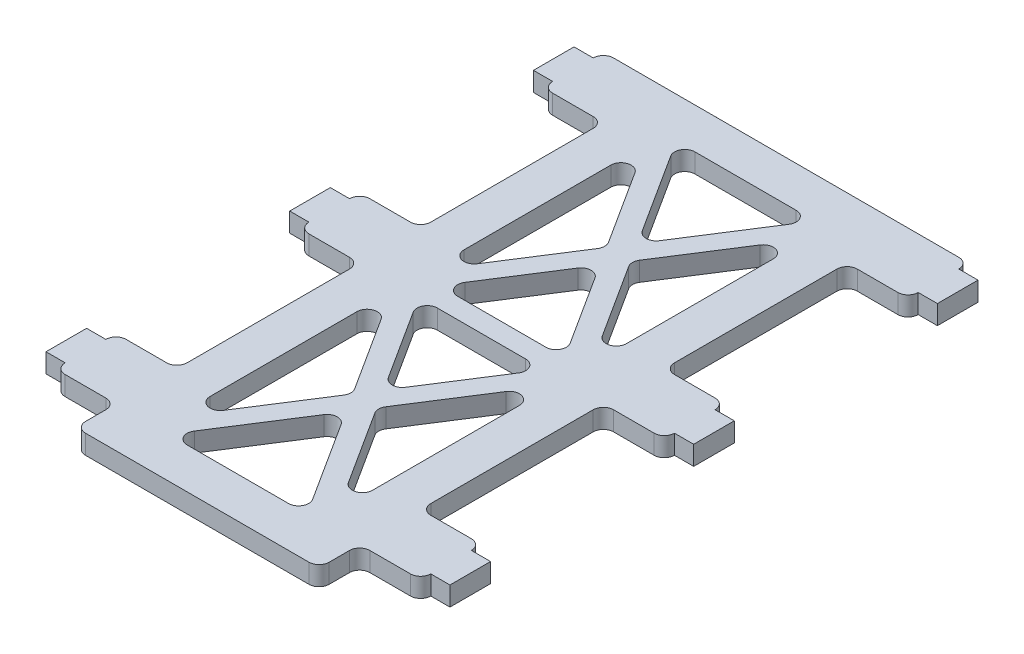
SolidWorks part; units mm, degrees
ref_plane "Front Plane" through (0, 0, 0) normal (0, 0, 1) x (1, 0, 0)
ref_plane "Top Plane" through (0, 0, 0) normal (0, 1, 0) x (1, 0, 0)
ref_plane "Right Plane" through (0, 0, 0) normal (1, 0, 0) x (0, 0, -1)
sketch "Sketch1" plane through (0, 34.29, 0) normal (0, 1, 0) x (1, 0, 0)
  line L0 (22.4028, 180.975) -> (25.4, 180.975) construction
  line L1 (0, -190.5) -> (0, 187.198) construction
  line L2 (38.1028, 187.198) -> (35.1028, 187.198) construction
  line L3 (35.1028, -190.5) -> (38.1, -190.5) construction
  line L5 (-19.05, 74.6125) -> (19.05, 74.6125)
  line L6 (-19.05, 74.6125) -> (-19.05, 166.6875)
  line L7 (-19.05, 166.6875) -> (19.05, 166.6875)
  line L8 (19.05, 74.6125) -> (19.05, 166.6875)
  line L9 (-19.05, 74.6125) -> (19.05, 166.6875) construction
  line L10 (-19.05, 166.6875) -> (19.05, 74.6125) construction
  point P0 (0, 120.65)
  dimension "D1" = 92.075
  dimension "D2" = 38.1
  dimension "D3" = 14.2875
extrude "Boss-Extrude1" add sketch "Sketch1" along normal mid plane 3 contours L7 L8 L5 L6
sketch "Sketch2" plane through (0, 35.79, 0) normal (0, 1, 0) x (1, 0, 0)
  line L0 (0, 166.6875) -> (0, 65.0186) construction
  line L1 (-19.05, 166.6875) -> (19.05, 166.6875) construction
  line L2 (19.05, 123.825) -> (-19.05, 123.825) construction
  line L5 (-28.575, 166.6875) -> (-19.05, 157.1625) construction
  line L6 (28.575, 157.1625) -> (19.05, 157.1625)
  line L7 (28.575, 157.1625) -> (28.575, 166.6875)
  line L8 (28.575, 166.6875) -> (19.05, 166.6875)
  line L9 (19.05, 157.1625) -> (19.05, 166.6875)
  line L10 (28.575, 157.1625) -> (19.05, 166.6875) construction
  line L11 (28.575, 166.6875) -> (19.05, 157.1625) construction
  line L12 (-28.575, 157.1625) -> (-19.05, 166.6875) construction
  line L13 (-19.05, 157.1625) -> (-19.05, 166.6875)
  line L14 (-28.575, 166.6875) -> (-19.05, 166.6875)
  line L15 (-28.575, 157.1625) -> (-28.575, 166.6875)
  line L16 (-28.575, 157.1625) -> (-19.05, 157.1625)
  line L17 (28.575, 119.0625) -> (19.05, 119.0625)
  line L18 (28.575, 119.0625) -> (28.575, 128.5875)
  line L19 (28.575, 128.5875) -> (19.05, 128.5875)
  line L20 (19.05, 119.0625) -> (19.05, 128.5875)
  line L21 (28.575, 119.0625) -> (19.05, 128.5875) construction
  line L22 (28.575, 128.5875) -> (19.05, 119.0625) construction
  line L23 (-19.05, 119.0625) -> (-19.05, 128.5875)
  line L24 (-28.575, 128.5875) -> (-19.05, 128.5875)
  line L25 (-28.575, 119.0625) -> (-28.575, 128.5875)
  line L26 (-28.575, 119.0625) -> (-19.05, 119.0625)
  line L27 (-28.575, 128.5875) -> (-19.05, 119.0625) construction
  line L28 (-28.575, 119.0625) -> (-19.05, 128.5875) construction
  line L29 (28.575, 80.9625) -> (19.05, 80.9625)
  line L30 (28.575, 80.9625) -> (28.575, 90.4875)
  line L31 (28.575, 90.4875) -> (19.05, 90.4875)
  line L32 (19.05, 80.9625) -> (19.05, 90.4875)
  line L33 (28.575, 80.9625) -> (19.05, 90.4875) construction
  line L34 (28.575, 90.4875) -> (19.05, 80.9625) construction
  line L35 (-19.05, 80.9625) -> (-19.05, 90.4875)
  line L36 (-28.575, 90.4875) -> (-19.05, 90.4875)
  line L37 (-28.575, 80.9625) -> (-28.575, 90.4875)
  line L38 (-28.575, 80.9625) -> (-19.05, 80.9625)
  line L39 (-28.575, 90.4875) -> (-19.05, 80.9625) construction
  line L40 (-28.575, 80.9625) -> (-19.05, 90.4875) construction
  point P11 (23.8125, 161.925)
  point P21 (-23.8125, 161.925)
  point P24 (23.8125, 123.825)
  point P33 (-23.8125, 123.825)
  point P34 (23.8125, 85.725)
  point P43 (-23.8125, 85.725)
  dimension "D1" = 9.525
  dimension "D2" = 9.525
  dimension "D4" = 38.1
  dimension "D3" = 3
extrude "Boss-Extrude2" add sketch "Sketch2" against normal up to surface (3 mm away) up to face at (0, 32.79, -120.65)
sketch "Sketch4" plane through (0, 35.79, 0) normal (0, 1, 0) x (1, 0, 0)
  line L0 (19.05, 128.5875) -> (19.05, 157.1625) construction
  line L1 (-12.7, 160.3375) -> (12.7, 160.3375)
  line L2 (-12.7, 160.3375) -> (-12.7, 80.9625)
  line L3 (-12.7, 80.9625) -> (12.7, 80.9625)
  line L4 (12.7, 160.3375) -> (12.7, 80.9625)
  line L5 (-12.7, 160.3375) -> (12.7, 80.9625) construction
  line L6 (-12.7, 80.9625) -> (12.7, 160.3375) construction
  line L7 (-19.05, 128.5875) -> (-19.05, 157.1625) construction
  line L8 (-28.575, 166.6875) -> (28.575, 166.6875) construction
  line L9 (-19.05, 74.6125) -> (19.05, 74.6125) construction
  line L10 (-12.7, 120.65) -> (12.7, 120.65) construction
  line L11 (12.7, 120.65) -> (-12.7, 160.3375) construction
  line L12 (12.7, 120.65) -> (-12.7, 80.9625) construction
  line L13 (-12.7, 120.65) -> (12.7, 160.3375) construction
  line L14 (12.7, 80.9625) -> (-12.7, 120.65) construction
  line L15 (-12.7, 119.0625) -> (12.7, 119.0625)
  line L16 (-12.7, 122.2375) -> (12.7, 122.2375)
  line L17 (14.0371, 81.8182) -> (-10.8152, 120.65)
  line L18 (-10.8152, 120.65) -> (14.0371, 159.4818)
  line L19 (14.5848, 120.65) -> (-11.3629, 80.1068)
  line L20 (14.5848, 120.65) -> (-11.3629, 161.1932)
  line L21 (11.3629, 80.1068) -> (-14.5848, 120.65)
  line L22 (-14.5848, 120.65) -> (11.3629, 161.1932)
  line L23 (10.8152, 120.65) -> (-14.0371, 81.8182)
  line L24 (10.8152, 120.65) -> (-14.0371, 159.4818)
  point P0 (0, 120.65)
  dimension "D1" = 6.35
  dimension "D2" = 6.35
  dimension "D3" = 6.35
  dimension "D4" = 6.35
  dimension "D5" = 1.5875
  dimension "D6" = 1.5875
  dimension "D7" = 1.5875
  dimension "D8" = 1.5875
extrude "Cut-Extrude1" cut sketch "Sketch4" against normal blind 3 contours L15 L19 L17 L4 | L3 L21 L19 | L23 L21 L15 L2 | L23 L15 L17 | L16 L24 L18 | L20 L16 L4 L18 | L20 L22 L1 | L22 L24 L2 L16
fillet "Fillet1" radius 1.5875 48 edges at (-9.7992, 34.29, -119.0625) (9.7992, 34.29, -119.0625) (0, 34.29, -103.7512) (-12.7, 34.29, -117.705) (-1.8848, 34.29, -100.8063) (-12.7, 34.29, -83.9075) (12.7, 34.29, -157.3925) (12.7, 34.29, -123.595) (1.8848, 34.29, -140.4938) (10.8152, 34.29, -160.3375) (0, 34.29, -143.4387) (-10.8152, 34.29, -160.3375) (1.8848, 34.29, -100.8063) (12.7, 34.29, -117.705) (12.7, 34.29, -83.9075) (28.575, 34.29, -80.9625) (28.575, 34.29, -90.4875) (19.05, 34.29, -90.4875) (19.05, 34.29, -119.0625) (28.575, 34.29, -119.0625) (28.575, 34.29, -128.5875) (19.05, 34.29, -128.5875) (19.05, 34.29, -157.1625) (28.575, 34.29, -157.1625) (28.575, 34.29, -166.6875) (-28.575, 34.29, -157.1625) (-19.05, 34.29, -157.1625) (-19.05, 34.29, -128.5875) (-28.575, 34.29, -128.5875) (-28.575, 34.29, -119.0625) (-19.05, 34.29, -119.0625) (-19.05, 34.29, -90.4875) (-28.575, 34.29, -90.4875) (-12.7, 34.29, -123.595) (-12.7, 34.29, -157.3925) (-1.8848, 34.29, -140.4938) (-10.8152, 34.29, -80.9625) (0, 34.29, -97.8613) (10.8152, 34.29, -80.9625) (-9.7992, 34.29, -122.2375) (0, 34.29, -137.5488) (9.7992, 34.29, -122.2375) (-28.575, 34.29, -166.6875) (-19.05, 34.29, -74.6125) (19.05, 34.29, -74.6125) (19.05, 34.29, -80.9625) (-28.575, 34.29, -80.9625) (-19.05, 34.29, -80.9625)
sketch "Sketch5" plane through (0, 35.79, 0) normal (0, 1, 0) x (1, 0, 0)
  line L0 (28.575, 158.75) -> (28.575, 165.1) construction
  line L1 (31.575, 158.75) -> (28.575, 158.75)
  line L2 (31.575, 158.75) -> (31.575, 165.1)
  line L3 (31.575, 165.1) -> (28.575, 165.1)
  line L4 (28.575, 158.75) -> (28.575, 165.1)
  line L5 (31.575, 158.75) -> (28.575, 165.1) construction
  line L6 (31.575, 165.1) -> (28.575, 158.75) construction
  line L7 (28.575, 158.75) -> (28.575, 165.1) construction
  line L8 (28.575, 161.925) -> (30.075, 161.925) construction
  line L9 (0, 196.0278) -> (0, 0) construction
  line L10 (-28.575, 161.925) -> (-30.075, 161.925) construction
  line L11 (-31.575, 165.1) -> (-28.575, 158.75) construction
  line L12 (-31.575, 158.75) -> (-28.575, 165.1) construction
  line L13 (-28.575, 158.75) -> (-28.575, 165.1)
  line L14 (-31.575, 165.1) -> (-28.575, 165.1)
  line L15 (-31.575, 158.75) -> (-31.575, 165.1)
  line L16 (-31.575, 158.75) -> (-28.575, 158.75)
  line L17 (31.575, 120.65) -> (28.575, 120.65)
  line L18 (31.575, 120.65) -> (31.575, 127)
  line L19 (31.575, 127) -> (28.575, 127)
  line L20 (28.575, 120.65) -> (28.575, 127)
  line L21 (31.575, 120.65) -> (28.575, 127) construction
  line L22 (31.575, 127) -> (28.575, 120.65) construction
  line L23 (28.575, 123.825) -> (30.075, 123.825) construction
  line L24 (-28.575, 120.65) -> (-28.575, 127)
  line L25 (-31.575, 127) -> (-28.575, 127)
  line L26 (-31.575, 120.65) -> (-31.575, 127)
  line L27 (-31.575, 120.65) -> (-28.575, 120.65)
  line L28 (-28.575, 123.825) -> (-30.075, 123.825) construction
  line L29 (-31.575, 127) -> (-28.575, 120.65) construction
  line L30 (-31.575, 120.65) -> (-28.575, 127) construction
  line L31 (31.575, 82.55) -> (28.575, 82.55)
  line L32 (31.575, 82.55) -> (31.575, 88.9)
  line L33 (31.575, 88.9) -> (28.575, 88.9)
  line L34 (28.575, 82.55) -> (28.575, 88.9)
  line L35 (31.575, 82.55) -> (28.575, 88.9) construction
  line L36 (31.575, 88.9) -> (28.575, 82.55) construction
  line L37 (28.575, 85.725) -> (30.075, 85.725) construction
  line L38 (-28.575, 82.55) -> (-28.575, 88.9)
  line L39 (-31.575, 88.9) -> (-28.575, 88.9)
  line L40 (-31.575, 82.55) -> (-31.575, 88.9)
  line L41 (-31.575, 82.55) -> (-28.575, 82.55)
  line L42 (-28.575, 85.725) -> (-30.075, 85.725) construction
  line L43 (-31.575, 88.9) -> (-28.575, 82.55) construction
  line L44 (-31.575, 82.55) -> (-28.575, 88.9) construction
  line L45 (-30.075, 161.925) -> (-30.075, 123.825) construction
  point P0 (30.075, 161.925)
  point P7 (30.075, 123.825)
  point P21 (-30.075, 161.925)
  point P35 (-30.075, 123.825)
  point P36 (30.075, 85.725)
  point P49 (-30.075, 85.725)
  dimension "D1" = 3
  dimension "D2" = 6.35
  dimension "D4" = 38.1
  dimension "D3" = 3
extrude "Boss-Extrude3" add sketch "Sketch5" against normal up to surface (3 mm away)
